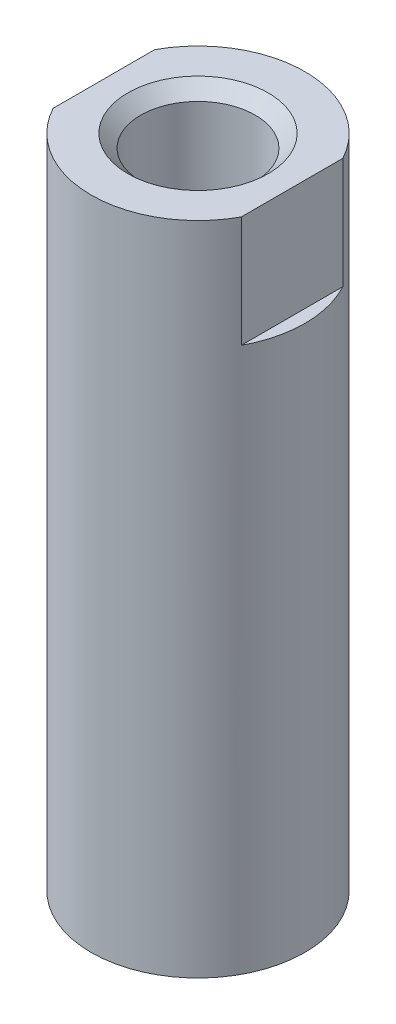
SolidWorks part; units mm, degrees
material "Chrome Stainless Steel"
ref_plane "Front Plane" through (0, 0, 0) normal (0, 0, 1) x (1, 0, 0)
ref_plane "Top Plane" through (0, 0, 0) normal (0, 1, 0) x (1, 0, 0)
ref_plane "Right Plane" through (0, 0, 0) normal (1, 0, 0) x (0, 0, -1)
ref_plane "Plane1" through (0, 0, 0) normal (0, 0, -1) x (-1, 0, 0)
sketch "Sketch1" plane through (0, 0, 0) normal (0, 0, -1) x (-1, 0, 0)
  line L0 (-3.175, 0) -> (0, 0)
  line L1 (0, 0) -> (0, 19.4818)
  line L2 (0, 19.4818) -> (-3.175, 19.4818)
  line L3 (-3.175, 19.4818) -> (-3.175, 0)
  line L4 (0, 0) -> (0, 19.4818) construction
revolve "Revolve1" add sketch "Sketch1" angle 360 about L4
sketch "Sketch2" plane through (0, 19.4818, 0) normal (0, 1, 0) x (-1, 0, 0)
  line L0 (2.794, 1.508) -> (2.794, -1.508)
  arc A0 (2.794, -1.508) -> (2.794, 1.508) centre (0, 0) ccw
extrude "Cut-Extrude1" cut sketch "Sketch2" against normal blind 3.302
sketch "Sketch3" plane through (0, 19.4818, 0) normal (0, 1, 0) x (-1, 0, 0)
  line L0 (-2.794, -1.508) -> (-2.794, 1.508)
  arc A0 (-2.794, 1.508) -> (-2.794, -1.508) centre (0, 0) ccw
extrude "Cut-Extrude2" cut sketch "Sketch3" against normal blind 3.302
hole_wizard "M3 Clearance Hole1" positions "Sketch5" profile "Sketch4" hole size "M3" standard "ANSI Metric"
sketch "Sketch5" plane through (0, 19.4818, 0) normal (0, 1, 0) x (1, 0, 0)
  point P0 (0, 0)
sketch "Sketch4" plane through (0, 19.4818, 0) normal (1, 0, 0) x (0, 0, 1)
  line L0 (0, 0) -> (0, 11.684)
  line L1 (0, 11.684) -> (1.7005, 11.684)
  line L2 (1.7005, 11.684) -> (1.7005, 0)
  line L5 (1.7005, 0) -> (0, 0)
  line L10 (0, 11.684) -> (-1.7005, 11.684) construction
  line L11 (0, -6.35) -> (0, 107.95) construction
  dimension "Hole Dia." = 3.4011
  dimension "Hole Depth" = 11.684
  dimension "Drill Angle" = 180
chamfer "Chamfer1" distance 0.3823 angle 45 1 edges at (0, 19.4818, 1.7005)
